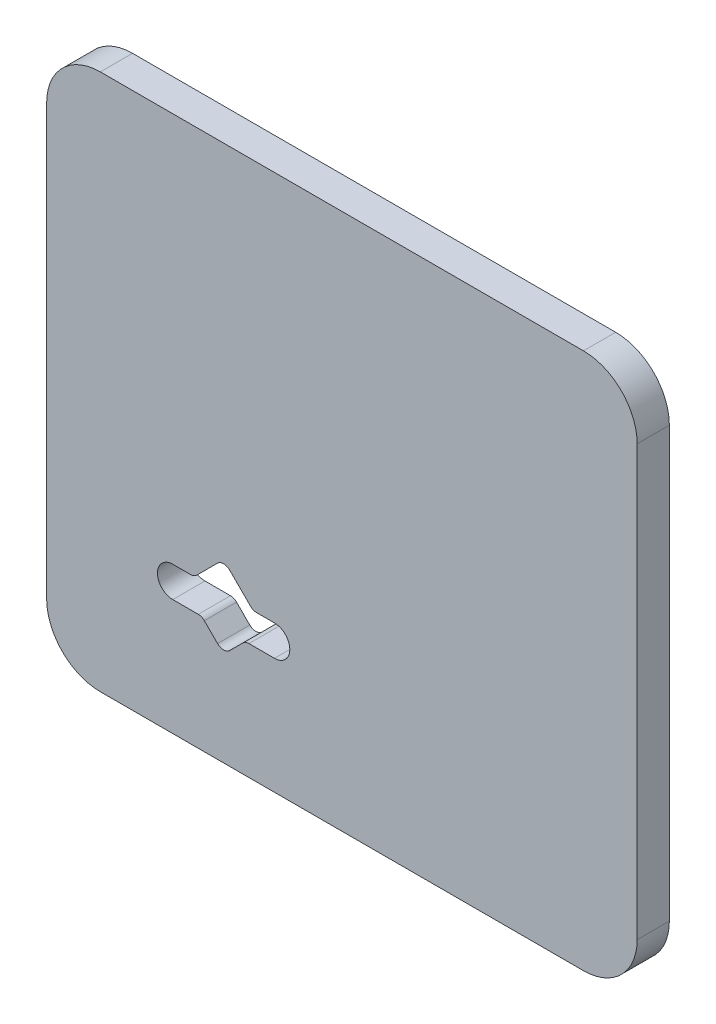
SolidWorks part; units mm, degrees
ref_plane "Front Plane" through (0, 0, 0) normal (0, 0, 1) x (1, 0, 0)
ref_plane "Top Plane" through (0, 0, 0) normal (0, 1, 0) x (1, 0, 0)
ref_plane "Right Plane" through (0, 0, 0) normal (1, 0, 0) x (0, 0, -1)
sketch "Sketch1" plane through (0, 0, 0) normal (0, 0, 1) x (1, 0, 0)
  line L0 (24.8331, 21.3616) -> (26.9523, 21.3616)
  line L2 (0, 10.3642) -> (0, 61.1642)
  line L3 (6.35, 67.5142) -> (63.5, 67.5142)
  line L4 (69.85, 61.1642) -> (69.85, 10.3642)
  line L5 (20.2159, 24.1211) -> (17.754, 21.6592)
  line L6 (18.6568, 17.4444) -> (20.2159, 15.8853)
  line L7 (21.6528, 15.8853) -> (23.2119, 17.4444)
  line L8 (24.1147, 21.6592) -> (21.6528, 24.1211)
  line L9 (14.9164, 21.3616) -> (17.0356, 21.3616)
  line L10 (23.9303, 17.742) -> (26.9523, 17.742)
  line L11 (14.9164, 17.742) -> (17.9384, 17.742)
  line L13 (63.5, 4.0142) -> (6.35, 4.0142)
  arc A0 (26.9523, 17.742) -> (26.9523, 21.3616) centre (26.9523, 19.5518) ccw
  arc A1 (14.9164, 21.3616) -> (14.9164, 17.742) centre (14.9164, 19.5518) ccw
  arc A2 (20.2159, 24.1211) -> (21.6528, 24.1211) centre (20.9343, 23.4027) cw
  arc A3 (20.2159, 15.8853) -> (21.6528, 15.8853) centre (20.9343, 16.6037) ccw
  arc A4 (23.2119, 17.4444) -> (23.9303, 17.742) centre (23.9303, 16.726) cw
  arc A5 (18.6568, 17.4444) -> (17.9384, 17.742) centre (17.9384, 16.726) ccw
  arc A6 (17.754, 21.6592) -> (17.0356, 21.3616) centre (17.0356, 22.3776) cw
  arc A7 (24.1147, 21.6592) -> (24.8331, 21.3616) centre (24.8331, 22.3776) ccw
  arc A8 (0, 61.1642) -> (6.35, 67.5142) centre (6.35, 61.1642) cw
  arc A9 (69.85, 61.1642) -> (63.5, 67.5142) centre (63.5, 61.1642) ccw
  arc A10 (63.5, 4.0142) -> (69.85, 10.3642) centre (63.5, 10.3642) ccw
  arc A11 (0, 10.3642) -> (6.35, 4.0142) centre (6.35, 10.3642) ccw
  point P23 (23.5094, 17.742)
  point P28 (17.4564, 21.3616)
  point P31 (24.4123, 21.3616)
  dimension "D1" = 2.54
  dimension "D3" = 1.016
  dimension "D4" = 6.35
  dimension "D2" = 2.54
  dimension "D5" = 69.85
  dimension "D6" = 63.5
extrude "Extrude1" add sketch "Sketch1" against normal blind 3.81
